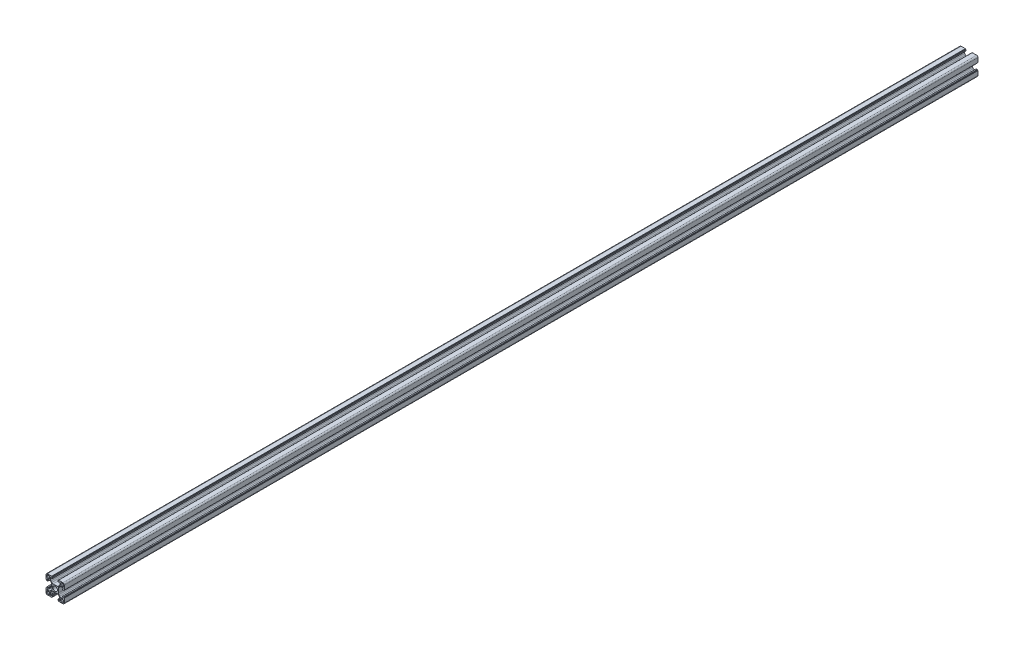
SolidWorks part; units mm, degrees
ref_plane "Front" through (0, 0, 0) normal (0, 0, 1) x (1, 0, 0)
ref_plane "Top" through (0, 0, 0) normal (0, 1, 0) x (1, 0, 0)
ref_plane "Right" through (0, 0, 0) normal (1, 0, 0) x (0, 0, -1)
sketch "Эскиз1" plane through (0, 0, 0) normal (0, 0, 1) x (1, 0, 0)
  line L0 (0, 13.9869) -> (0, 0) construction
  line L5 (-8.5, 10) -> (-3.85, 10)
  line L9 (9.1, 9.1) -> (6.1, 6.1) construction
  line L10 (-3.05, 9.3991) -> (-3.05, 8.25)
  line L11 (-11.4953, 0) -> (0, 0) construction
  line L12 (-3.7, 9.85) -> (-3.7, 9.5491)
  line L13 (-2.2473, 3.5) -> (-0.9681, 3.5)
  line L14 (-0.9681, 3.5) -> (0.9681, 3.5)
  line L15 (-4.6142, 5.0385) -> (-3.6615, 4.0858)
  line L16 (0, 11.4953) -> (0, 0) construction
  line L17 (-4.5971, 8.7) -> (-4.7, 8.7)
  line L18 (-3.5864, 8) -> (-3.3, 8)
  line L19 (-3.2, 9.5491) -> (-3.7, 9.5491)
  line L20 (-3.7632, 8.0732) -> (-4.2436, 8.5536)
  line L21 (-5.2, 8.2) -> (-5.2, 6.4527)
  line L22 (-8.2, 5.2) -> (-6.4527, 5.2)
  line L23 (-8.0732, 3.7632) -> (-8.5536, 4.2436)
  line L24 (-9.5491, 3.2) -> (-9.5491, 3.7)
  line L25 (-8, 3.5864) -> (-8, 3.3)
  line L26 (-8.7, 4.5971) -> (-8.7, 4.7)
  line L27 (-5.0385, 4.6142) -> (-4.0858, 3.6615)
  line L28 (-3.5, 0.9681) -> (-3.5, -0.9681)
  line L29 (-3.5, 2.2473) -> (-3.5, 0.9681)
  line L30 (-9.85, 3.7) -> (-9.5491, 3.7)
  line L31 (-9.3991, 3.05) -> (-8.25, 3.05)
  line L32 (-10, 8.5) -> (-10, 3.85)
  line L33 (9.1, 6.1) -> (6.1, 9.1) construction
  line L34 (-8.3, 6.1) -> (-6.9, 6.1)
  line L35 (-9.1, 6.9) -> (-9.1, 8.3)
  line L36 (-8.3, 9.1) -> (-6.9, 9.1)
  line L37 (-6.1, 6.9) -> (-6.1, 8.3)
  line L38 (-9.1, 6.1) -> (-6.1, 9.1) construction
  line L39 (-9.1, 9.1) -> (-6.1, 6.1) construction
  line L40 (6.1, 6.9) -> (6.1, 8.3)
  line L41 (8.3, 9.1) -> (6.9, 9.1)
  line L42 (9.1, 6.9) -> (9.1, 8.3)
  line L43 (8.3, 6.1) -> (6.9, 6.1)
  line L44 (10, 8.5) -> (10, 3.85)
  line L45 (9.3991, 3.05) -> (8.25, 3.05)
  line L46 (9.85, 3.7) -> (9.5491, 3.7)
  line L47 (3.5, 2.2473) -> (3.5, 0.9681)
  line L48 (3.5, 0.9681) -> (3.5, -0.9681)
  line L49 (5.0385, 4.6142) -> (4.0858, 3.6615)
  line L50 (8.7, 4.5971) -> (8.7, 4.7)
  line L51 (8, 3.5864) -> (8, 3.3)
  line L52 (9.5491, 3.2) -> (9.5491, 3.7)
  line L53 (8.0732, 3.7632) -> (8.5536, 4.2436)
  line L54 (8.2, 5.2) -> (6.4527, 5.2)
  line L55 (5.2, 8.2) -> (5.2, 6.4527)
  line L56 (3.7632, 8.0732) -> (4.2436, 8.5536)
  line L57 (3.2, 9.5491) -> (3.7, 9.5491)
  line L58 (3.5864, 8) -> (3.3, 8)
  line L59 (4.5971, 8.7) -> (4.7, 8.7)
  line L60 (4.6142, 5.0385) -> (3.6615, 4.0858)
  line L61 (2.2473, 3.5) -> (0.9681, 3.5)
  line L62 (3.7, 9.85) -> (3.7, 9.5491)
  line L63 (3.05, 9.3991) -> (3.05, 8.25)
  line L64 (8.5, 10) -> (3.85, 10)
  line L65 (-9.1, -9.1) -> (-6.1, -6.1) construction
  line L66 (-9.1, -6.1) -> (-6.1, -9.1) construction
  line L67 (9.1, -6.1) -> (6.1, -9.1) construction
  line L68 (9.1, -9.1) -> (6.1, -6.1) construction
  line L69 (8.5, -10) -> (3.85, -10)
  line L70 (3.05, -9.3991) -> (3.05, -8.25)
  line L71 (3.7, -9.85) -> (3.7, -9.5491)
  line L72 (2.2473, -3.5) -> (0.9681, -3.5)
  line L73 (4.6142, -5.0385) -> (3.6615, -4.0858)
  line L74 (4.5971, -8.7) -> (4.7, -8.7)
  line L75 (3.5864, -8) -> (3.3, -8)
  line L76 (3.2, -9.5491) -> (3.7, -9.5491)
  line L77 (3.7632, -8.0732) -> (4.2436, -8.5536)
  line L78 (5.2, -8.2) -> (5.2, -6.4527)
  line L79 (8.2, -5.2) -> (6.4527, -5.2)
  line L80 (8.0732, -3.7632) -> (8.5536, -4.2436)
  line L81 (9.5491, -3.2) -> (9.5491, -3.7)
  line L82 (8, -3.5864) -> (8, -3.3)
  line L83 (8.7, -4.5971) -> (8.7, -4.7)
  line L84 (5.0385, -4.6142) -> (4.0858, -3.6615)
  line L85 (3.5, -2.2473) -> (3.5, -0.9681)
  line L86 (9.85, -3.7) -> (9.5491, -3.7)
  line L87 (9.3991, -3.05) -> (8.25, -3.05)
  line L88 (10, -8.5) -> (10, -3.85)
  line L89 (8.3, -6.1) -> (6.9, -6.1)
  line L90 (9.1, -6.9) -> (9.1, -8.3)
  line L91 (8.3, -9.1) -> (6.9, -9.1)
  line L92 (6.1, -6.9) -> (6.1, -8.3)
  line L93 (-6.1, -6.9) -> (-6.1, -8.3)
  line L94 (-8.3, -9.1) -> (-6.9, -9.1)
  line L95 (-9.1, -6.9) -> (-9.1, -8.3)
  line L96 (-8.3, -6.1) -> (-6.9, -6.1)
  line L97 (-10, -8.5) -> (-10, -3.85)
  line L98 (-9.3991, -3.05) -> (-8.25, -3.05)
  line L99 (-9.85, -3.7) -> (-9.5491, -3.7)
  line L100 (-3.5, -2.2473) -> (-3.5, -0.9681)
  line L101 (-5.0385, -4.6142) -> (-4.0858, -3.6615)
  line L102 (-8.7, -4.5971) -> (-8.7, -4.7)
  line L103 (-8, -3.5864) -> (-8, -3.3)
  line L104 (-9.5491, -3.2) -> (-9.5491, -3.7)
  line L105 (-8.0732, -3.7632) -> (-8.5536, -4.2436)
  line L106 (-8.2, -5.2) -> (-6.4527, -5.2)
  line L107 (-5.2, -8.2) -> (-5.2, -6.4527)
  line L108 (-3.7632, -8.0732) -> (-4.2436, -8.5536)
  line L109 (-3.2, -9.5491) -> (-3.7, -9.5491)
  line L110 (-3.5864, -8) -> (-3.3, -8)
  line L111 (-4.5971, -8.7) -> (-4.7, -8.7)
  line L112 (-4.6142, -5.0385) -> (-3.6615, -4.0858)
  line L113 (-0.9681, -3.5) -> (0.9681, -3.5)
  line L114 (-2.2473, -3.5) -> (-0.9681, -3.5)
  line L115 (-3.7, -9.85) -> (-3.7, -9.5491)
  line L116 (-3.05, -9.3991) -> (-3.05, -8.25)
  line L117 (-8.5, -10) -> (-3.85, -10)
  circle A1 centre (0, 0) radius 2.5
  arc A3 (-3.6615, 4.0858) -> (-2.2473, 3.5) centre (-2.2473, 5.5) ccw
  arc A4 (-5.2, 6.4527) -> (-4.6142, 5.0385) centre (-3.2, 6.4527) ccw
  arc A5 (-4.7, 8.7) -> (-5.2, 8.2) centre (-4.7, 8.2) ccw
  arc A6 (-4.2436, 8.5536) -> (-4.5971, 8.7) centre (-4.5971, 8.2) ccw
  arc A7 (-3.3, 8) -> (-3.05, 8.25) centre (-3.3, 8.25) ccw
  arc A8 (-3.5864, 8) -> (-3.7632, 8.0732) centre (-3.5864, 8.25) cw
  arc A9 (-3.85, 10) -> (-3.7, 9.85) centre (-3.85, 9.85) cw
  arc A10 (-3.2, 9.5491) -> (-3.05, 9.3991) centre (-3.2, 9.3991) cw
  arc A11 (-9.5491, 3.2) -> (-9.3991, 3.05) centre (-9.3991, 3.2) ccw
  arc A12 (-10, 3.85) -> (-9.85, 3.7) centre (-9.85, 3.85) ccw
  arc A13 (-8, 3.5864) -> (-8.0732, 3.7632) centre (-8.25, 3.5864) ccw
  arc A14 (-8, 3.3) -> (-8.25, 3.05) centre (-8.25, 3.3) cw
  arc A15 (-8.5536, 4.2436) -> (-8.7, 4.5971) centre (-8.2, 4.5971) cw
  arc A16 (-8.7, 4.7) -> (-8.2, 5.2) centre (-8.2, 4.7) cw
  arc A17 (-6.4527, 5.2) -> (-5.0385, 4.6142) centre (-6.4527, 3.2) cw
  arc A18 (-4.0858, 3.6615) -> (-3.5, 2.2473) centre (-5.5, 2.2473) cw
  arc A19 (-8.5, 10) -> (-10, 8.5) centre (-8.5, 8.5) ccw
  arc A20 (-6.9, 6.1) -> (-6.1, 6.9) centre (-6.9, 6.9) ccw
  arc A21 (-8.3, 6.1) -> (-9.1, 6.9) centre (-8.3, 6.9) cw
  arc A22 (-6.9, 9.1) -> (-6.1, 8.3) centre (-6.9, 8.3) cw
  arc A23 (-9.1, 8.3) -> (-8.3, 9.1) centre (-8.3, 8.3) cw
  arc A24 (9.1, 8.3) -> (8.3, 9.1) centre (8.3, 8.3) ccw
  arc A25 (6.9, 9.1) -> (6.1, 8.3) centre (6.9, 8.3) ccw
  arc A26 (8.3, 6.1) -> (9.1, 6.9) centre (8.3, 6.9) ccw
  arc A27 (6.9, 6.1) -> (6.1, 6.9) centre (6.9, 6.9) cw
  arc A28 (8.5, 10) -> (10, 8.5) centre (8.5, 8.5) cw
  arc A29 (4.0858, 3.6615) -> (3.5, 2.2473) centre (5.5, 2.2473) ccw
  arc A30 (6.4527, 5.2) -> (5.0385, 4.6142) centre (6.4527, 3.2) ccw
  arc A31 (8.7, 4.7) -> (8.2, 5.2) centre (8.2, 4.7) ccw
  arc A32 (8.5536, 4.2436) -> (8.7, 4.5971) centre (8.2, 4.5971) ccw
  arc A33 (8, 3.3) -> (8.25, 3.05) centre (8.25, 3.3) ccw
  arc A34 (8, 3.5864) -> (8.0732, 3.7632) centre (8.25, 3.5864) cw
  arc A35 (10, 3.85) -> (9.85, 3.7) centre (9.85, 3.85) cw
  arc A36 (9.5491, 3.2) -> (9.3991, 3.05) centre (9.3991, 3.2) cw
  arc A37 (3.2, 9.5491) -> (3.05, 9.3991) centre (3.2, 9.3991) ccw
  arc A38 (3.85, 10) -> (3.7, 9.85) centre (3.85, 9.85) ccw
  arc A39 (3.5864, 8) -> (3.7632, 8.0732) centre (3.5864, 8.25) ccw
  arc A40 (3.3, 8) -> (3.05, 8.25) centre (3.3, 8.25) cw
  arc A41 (4.2436, 8.5536) -> (4.5971, 8.7) centre (4.5971, 8.2) cw
  arc A42 (4.7, 8.7) -> (5.2, 8.2) centre (4.7, 8.2) cw
  arc A43 (5.2, 6.4527) -> (4.6142, 5.0385) centre (3.2, 6.4527) cw
  arc A44 (3.6615, 4.0858) -> (2.2473, 3.5) centre (2.2473, 5.5) cw
  arc A45 (3.6615, -4.0858) -> (2.2473, -3.5) centre (2.2473, -5.5) ccw
  arc A46 (5.2, -6.4527) -> (4.6142, -5.0385) centre (3.2, -6.4527) ccw
  arc A47 (4.7, -8.7) -> (5.2, -8.2) centre (4.7, -8.2) ccw
  arc A48 (4.2436, -8.5536) -> (4.5971, -8.7) centre (4.5971, -8.2) ccw
  arc A49 (3.3, -8) -> (3.05, -8.25) centre (3.3, -8.25) ccw
  arc A50 (3.5864, -8) -> (3.7632, -8.0732) centre (3.5864, -8.25) cw
  arc A51 (3.85, -10) -> (3.7, -9.85) centre (3.85, -9.85) cw
  arc A52 (3.2, -9.5491) -> (3.05, -9.3991) centre (3.2, -9.3991) cw
  arc A53 (9.5491, -3.2) -> (9.3991, -3.05) centre (9.3991, -3.2) ccw
  arc A54 (10, -3.85) -> (9.85, -3.7) centre (9.85, -3.85) ccw
  arc A55 (8, -3.5864) -> (8.0732, -3.7632) centre (8.25, -3.5864) ccw
  arc A56 (8, -3.3) -> (8.25, -3.05) centre (8.25, -3.3) cw
  arc A57 (8.5536, -4.2436) -> (8.7, -4.5971) centre (8.2, -4.5971) cw
  arc A58 (8.7, -4.7) -> (8.2, -5.2) centre (8.2, -4.7) cw
  arc A59 (6.4527, -5.2) -> (5.0385, -4.6142) centre (6.4527, -3.2) cw
  arc A60 (4.0858, -3.6615) -> (3.5, -2.2473) centre (5.5, -2.2473) cw
  arc A61 (8.5, -10) -> (10, -8.5) centre (8.5, -8.5) ccw
  arc A62 (6.9, -6.1) -> (6.1, -6.9) centre (6.9, -6.9) ccw
  arc A63 (8.3, -6.1) -> (9.1, -6.9) centre (8.3, -6.9) cw
  arc A64 (6.9, -9.1) -> (6.1, -8.3) centre (6.9, -8.3) cw
  arc A65 (9.1, -8.3) -> (8.3, -9.1) centre (8.3, -8.3) cw
  arc A66 (-9.1, -8.3) -> (-8.3, -9.1) centre (-8.3, -8.3) ccw
  arc A67 (-6.9, -9.1) -> (-6.1, -8.3) centre (-6.9, -8.3) ccw
  arc A68 (-8.3, -6.1) -> (-9.1, -6.9) centre (-8.3, -6.9) ccw
  arc A69 (-6.9, -6.1) -> (-6.1, -6.9) centre (-6.9, -6.9) cw
  arc A70 (-8.5, -10) -> (-10, -8.5) centre (-8.5, -8.5) cw
  arc A71 (-4.0858, -3.6615) -> (-3.5, -2.2473) centre (-5.5, -2.2473) ccw
  arc A72 (-6.4527, -5.2) -> (-5.0385, -4.6142) centre (-6.4527, -3.2) ccw
  arc A73 (-8.7, -4.7) -> (-8.2, -5.2) centre (-8.2, -4.7) ccw
  arc A74 (-8.5536, -4.2436) -> (-8.7, -4.5971) centre (-8.2, -4.5971) ccw
  arc A75 (-8, -3.3) -> (-8.25, -3.05) centre (-8.25, -3.3) ccw
  arc A76 (-8, -3.5864) -> (-8.0732, -3.7632) centre (-8.25, -3.5864) cw
  arc A77 (-10, -3.85) -> (-9.85, -3.7) centre (-9.85, -3.85) cw
  arc A78 (-9.5491, -3.2) -> (-9.3991, -3.05) centre (-9.3991, -3.2) cw
  arc A79 (-3.2, -9.5491) -> (-3.05, -9.3991) centre (-3.2, -9.3991) ccw
  arc A80 (-3.85, -10) -> (-3.7, -9.85) centre (-3.85, -9.85) ccw
  arc A81 (-3.5864, -8) -> (-3.7632, -8.0732) centre (-3.5864, -8.25) ccw
  arc A82 (-3.3, -8) -> (-3.05, -8.25) centre (-3.3, -8.25) cw
  arc A83 (-4.2436, -8.5536) -> (-4.5971, -8.7) centre (-4.5971, -8.2) cw
  arc A84 (-4.7, -8.7) -> (-5.2, -8.2) centre (-4.7, -8.2) cw
  arc A85 (-5.2, -6.4527) -> (-4.6142, -5.0385) centre (-3.2, -6.4527) cw
  arc A86 (-3.6615, -4.0858) -> (-2.2473, -3.5) centre (-2.2473, -5.5) cw
  point P0 (0, 0)
  point P3 (-3.7, 8.7)
  point P17 (8.7, 3.7)
  point P67 (-8.7, 3.7)
  point P155 (0, 3.5)
  point P156 (3.7, 8.7)
  point P294 (3.5, 0)
  point P296 (-3.5, 0)
  point P298 (3.7, -8.7)
  point P299 (0, -3.5)
  point P300 (-8.7, -3.7)
  point P301 (8.7, -3.7)
  point P302 (-3.7, -8.7)
  dimension "D3" = 6.5
  dimension "D7" = 0.8
  dimension "D5" = 0.9
  dimension "D6" = 0.9
  dimension "D9" = 2
  dimension "D10" = 2
  dimension "D11" = 0.5
  dimension "D12" = 0.5
  dimension "D14" = 0.25
  dimension "D15" = 0.15
  dimension "D16" = 1.5
  dimension "D1" = 3.05
  dimension "D2" = 3.7
  dimension "D4" = 0.9
  dimension "D8" = 1.3
  dimension "D13" = 45
extrude "Бобышка-Вытянуть1" add sketch "Эскиз1" along normal blind 1000
